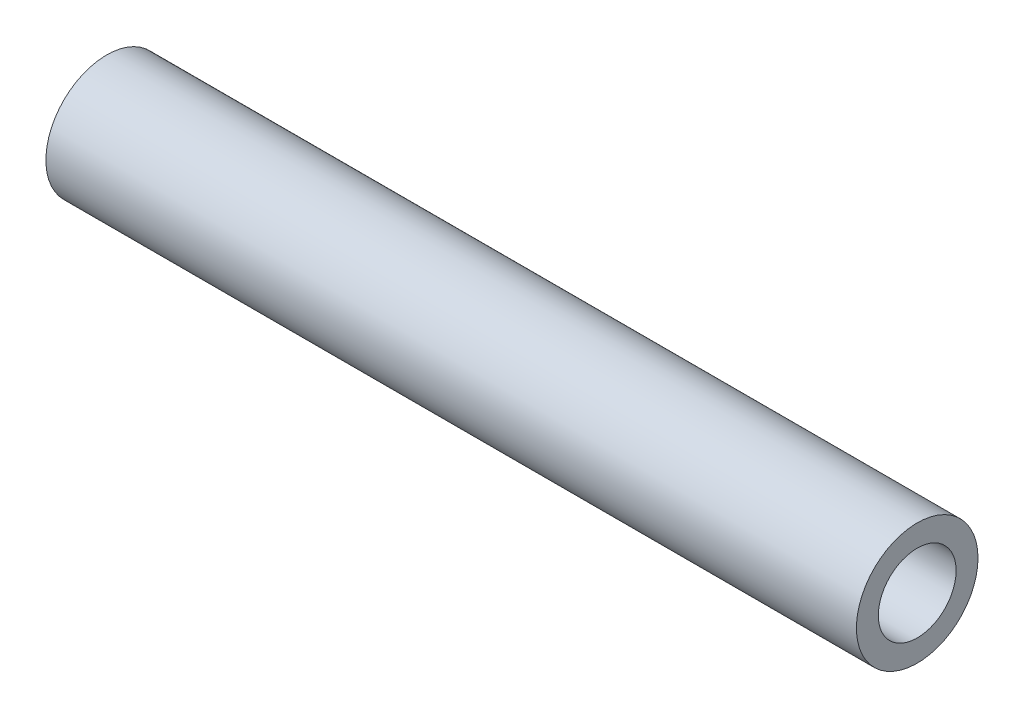
SolidWorks part; units mm, degrees
material "6061-T6 (SS)"
ref_plane "Front Plane" through (0, 0, 0) normal (0, 0, 1) x (1, 0, 0)
ref_plane "Top Plane" through (0, 0, 0) normal (0, 1, 0) x (1, 0, 0)
ref_plane "Right Plane" through (0, 0, 0) normal (1, 0, 0) x (0, 0, -1)
sketch "Sketch1" plane through (0, 0, 0) normal (1, 0, 0) x (0, 0, -1)
  circle A0 centre (0, 0) radius 2.4384
  circle A1 centre (0, 0) radius 3.81
  dimension "D1" = 7.62
  dimension "D2" = 4.8768
extrude "Boss-Extrude1" add sketch "Sketch1" along normal blind 50.8
